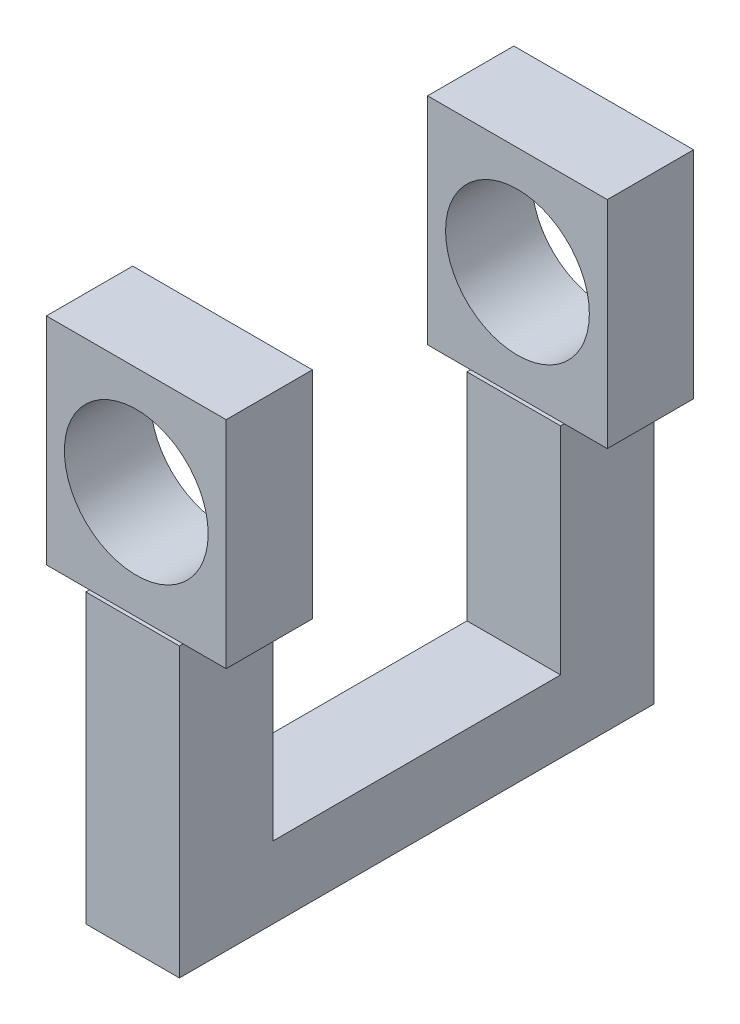
SolidWorks part; units mm, degrees
material "1023 Carbon Steel Sheet (SS)"
ref_plane "Front Plane" through (0, 0, 0) normal (0, 0, 1) x (1, 0, 0)
ref_plane "Top Plane" through (0, 0, 0) normal (0, 1, 0) x (1, 0, 0)
ref_plane "Right Plane" through (0, 0, 0) normal (1, 0, 0) x (0, 0, -1)
sketch "Sketch1" plane through (0, 0, 0) normal (0, 1, 0) x (1, 0, 0)
  line L1 (0, 0) -> (13.022, 0)
  line L2 (0, 0) -> (0, 40)
  line L3 (0, 40) -> (13.022, 40)
  line L4 (13.022, 0) -> (13.022, 40)
  dimension "D1" = 13.022
  dimension "D2" = 40
extrude "Boss-Extrude1" add sketch "Sketch1" along normal blind 10
sketch "Sketch2" plane through (0, 10, 0) normal (0, 1, 0) x (1, 0, 0)
  line L0 (13.022, 0) -> (13.022, 40) construction
  line L1 (0, 40) -> (13.022, 40)
  line L2 (0, 40) -> (0, 53.022)
  line L3 (0, 53.022) -> (13.022, 53.022)
  line L4 (13.022, 40) -> (13.022, 53.022)
  line L5 (0, 0) -> (13.022, 0)
  line L6 (0, 0) -> (0, -13.022)
  line L7 (0, -13.022) -> (13.022, -13.022)
  line L8 (13.022, 0) -> (13.022, -13.022)
  dimension "D2" = 13.022
  dimension "D3" = 13.022
extrude "Boss-Extrude2" add sketch "Sketch2" along normal blind 30 and the other way blind 10
sketch "Sketch3" plane through (0, 40, 0) normal (0, 1, 0) x (1, 0, 0)
  line L0 (13.022, 53.022) -> (0, 53.022) construction
  line L1 (1.06, 51.962) -> (11.962, 51.962)
  line L2 (1.06, 51.962) -> (1.06, 41.06)
  line L3 (1.06, 41.06) -> (11.962, 41.06)
  line L4 (11.962, 51.962) -> (11.962, 41.06)
  line L5 (1.06, -1.06) -> (11.962, -1.06)
  line L6 (1.06, -1.06) -> (1.06, -11.962)
  line L7 (1.06, -11.962) -> (11.962, -11.962)
  line L8 (11.962, -1.06) -> (11.962, -11.962)
  line L9 (13.022, 40) -> (0, 40) construction
  line L10 (13.022, 40) -> (13.022, 53.022) construction
  line L11 (0, 53.022) -> (0, 40) construction
  line L12 (0, 0) -> (13.022, 0) construction
  line L13 (13.022, -13.022) -> (13.022, 0) construction
  line L14 (0, -13.022) -> (13.022, -13.022) construction
  line L15 (0, 0) -> (0, -13.022) construction
  dimension "D1" = 1.06
  dimension "D2" = 1.06
  dimension "D3" = 1.06
  dimension "D4" = 1.06
  dimension "D5" = 1.06
  dimension "D6" = 1.06
  dimension "D7" = 1.06
  dimension "D8" = 1.06
extrude "Cut-Extrude1" cut sketch "Sketch3" against normal blind 50
sketch "Sketch4" plane through (0, 10, 0) normal (0, 1, 0) x (1, 0, 0)
  line L1 (1.06, 51.962) -> (11.962, 51.962)
  line L2 (1.06, 51.962) -> (1.06, 41.06)
  line L3 (1.06, 41.06) -> (11.962, 41.06)
  line L4 (11.962, 51.962) -> (11.962, 41.06)
  line L5 (1.06, -1.06) -> (11.962, -1.06)
  line L6 (1.06, -1.06) -> (1.06, -11.962)
  line L7 (1.06, -11.962) -> (11.962, -11.962)
  line L8 (11.962, -1.06) -> (11.962, -11.962)
extrude "Boss-Extrude3" add sketch "Sketch4" along normal blind 15 from offset 15
sketch "Sketch5" plane through (0, 40, 0) normal (0, 1, 0) x (1, 0, 0)
  line L1 (-5.989, 40.511) -> (19.011, 40.511)
  line L2 (-5.989, 40.511) -> (-5.989, 52.511)
  line L3 (-5.989, 52.511) -> (19.011, 52.511)
  line L4 (19.011, 40.511) -> (19.011, 52.511)
  line L5 (-5.989, 40.511) -> (19.011, 52.511) construction
  line L6 (-5.989, 52.511) -> (19.011, 40.511) construction
  line L7 (-5.989, -12.511) -> (19.011, -12.511)
  line L8 (-5.989, -12.511) -> (-5.989, -0.511)
  line L9 (-5.989, -0.511) -> (19.011, -0.511)
  line L10 (19.011, -12.511) -> (19.011, -0.511)
  line L11 (-5.989, -12.511) -> (19.011, -0.511) construction
  line L12 (-5.989, -0.511) -> (19.011, -12.511) construction
  line L13 (13.022, 53.022) -> (0, 40) construction
  line L14 (0, 40) -> (13.022, 40) construction
  line L15 (13.022, 40) -> (0, 53.022) construction
  line L16 (0, 53.022) -> (13.022, 53.022) construction
  line L17 (13.022, 0) -> (0, -13.022) construction
  line L18 (0, -13.022) -> (13.022, -13.022) construction
  line L19 (13.022, -13.022) -> (0, 0) construction
  line L20 (0, 0) -> (13.022, 0) construction
  point P0 (6.511, 46.511)
  point P5 (6.511, -6.511)
  point P10 (6.511, 46.511)
  point P28 (6.511, -6.511)
  dimension "D1" = 25
  dimension "D2" = 12
  dimension "D3" = 25
  dimension "D4" = 12
extrude "Boss-Extrude4" add sketch "Sketch5" along normal blind 30
sketch "Sketch6" plane through (0, 0, 12.511) normal (0, 0, 1) x (1, 0, 0)
  line L0 (-5.989, 40) -> (19.011, 70) construction
  line L1 (19.011, 70) -> (-5.989, 70) construction
  line L2 (-5.989, 70) -> (19.011, 40) construction
  circle A0 centre (6.511, 55) radius 10
  dimension "D1" = 20
extrude "Cut-Extrude2" cut sketch "Sketch6" against normal blind 100
